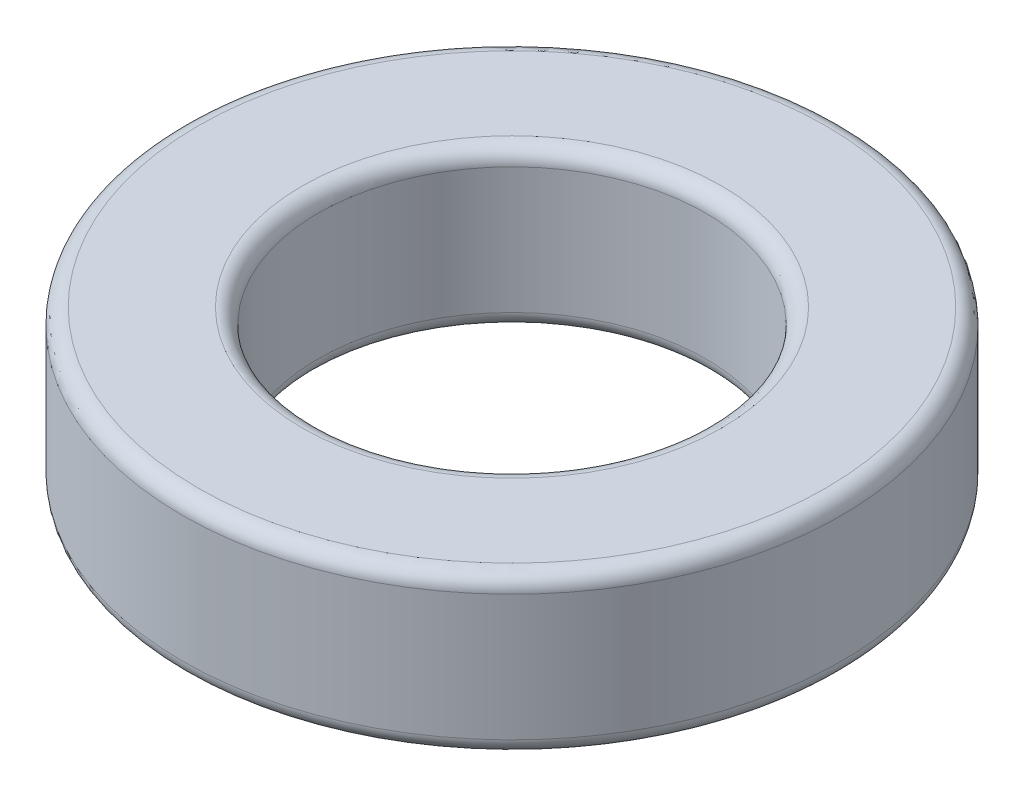
SolidWorks part; units mm, degrees
ref_plane "Спереди" through (0, 0, 0) normal (0, 0, 1) x (1, 0, 0)
ref_plane "Сверху" through (0, 0, 0) normal (0, 1, 0) x (1, 0, 0)
ref_plane "Справа" through (0, 0, 0) normal (1, 0, 0) x (0, 0, -1)
sketch "Эскиз1" plane through (0, 0, 0) normal (0, 1, 0) x (1, 0, 0)
  circle A0 centre (0, 0) radius 6.15
  circle A1 centre (0, 0) radius 10.45
  dimension "D1" = 12.3
  dimension "D2" = 20.9
extrude "Бобышка-Вытянуть1" add sketch "Эскиз1" along normal blind 5
fillet "Скругление1" radius 0.5 4 edges at (0, 5, 6.15) (0, 0, 6.15) (0, 0, 10.45) (0, 5, 10.45)
